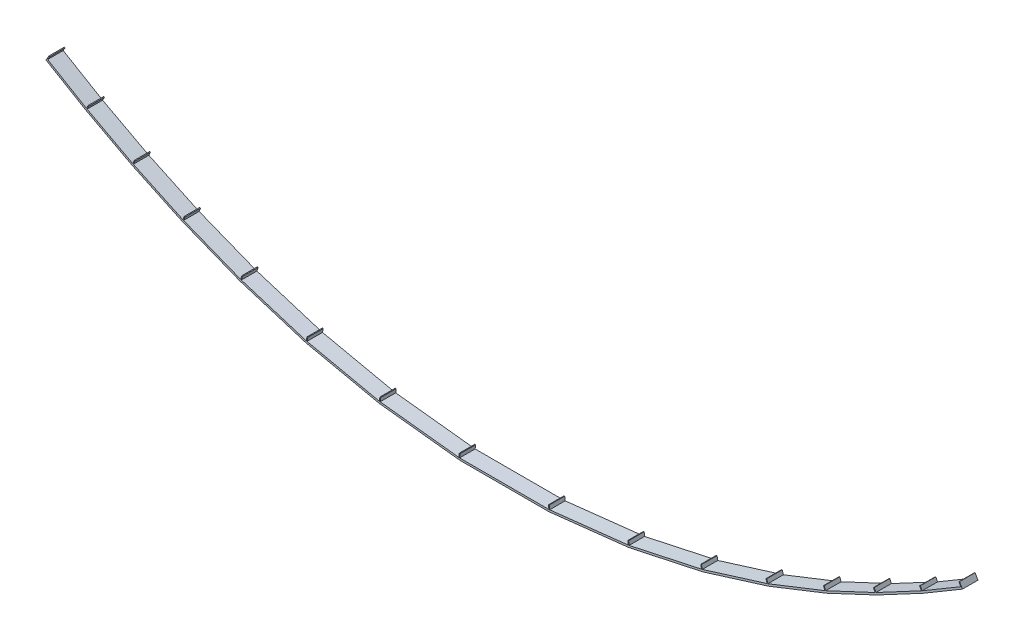
SolidWorks part; units mm, degrees
ref_plane "前视基准面" through (0, 0, 0) normal (0, 0, 1) x (1, 0, 0)
ref_plane "上视基准面" through (0, 0, 0) normal (0, 1, 0) x (1, 0, 0)
ref_plane "右视基准面" through (0, 0, 0) normal (1, 0, 0) x (0, 0, -1)
other "Configuration Table"
sketch "草图1" plane through (0, 0, 0) normal (0, 0, 1) x (1, 0, 0)
  line L0 (-115, 0) -> (115, 0)
  line L1 (-115, 0) -> (-321.7118, 23.1134)
  line L2 (-321.7118, 23.1134) -> (-510.3602, 63.8661)
  line L3 (-510.3602, 63.8661) -> (-679.3804, 116.413)
  line L4 (-679.3804, 116.413) -> (-828.1857, 175.2091)
  line L5 (-828.1857, 175.2091) -> (-957.6609, 235.9148)
  line L6 (-957.6609, 235.9148) -> (-1076.8145, 299.3766)
  line L7 (-1076.8145, 299.3766) -> (-1178.3926, 359.4258)
  line L8 (-1079.2632, 295.0159) -> (-1180.937, 355.1216)
  line L9 (-959.8988, 231.4418) -> (-1079.2632, 295.0159)
  line L10 (-830.1676, 170.616) -> (-959.8988, 231.4418)
  line L11 (-681.0436, 111.694) -> (-830.1676, 170.616)
  line L12 (-511.6328, 59.0257) -> (-681.0436, 111.694)
  line L13 (-322.5196, 18.1725) -> (-511.6328, 59.0257)
  line L14 (-115.2787, -5) -> (-322.5196, 18.1725)
  line L15 (-115.2787, -5) -> (115, -5)
  line L16 (115, 0) -> (115, -5)
  line L17 (0, 0) -> (0, -3) construction
  line L18 (-1178.3926, 359.4258) -> (-1180.937, 355.1216)
  dimension "D1" = 230
  dimension "D2" = 115
  dimension "D3" = 208
  dimension "D4" = 173.62
  dimension "D5" = 167.81
  dimension "D6" = 193
  dimension "D7" = 162.73
  dimension "D8" = 177
  dimension "D9" = 158.44
  dimension "D10" = 160
  dimension "D11" = 154.88
  dimension "D12" = 143
  dimension "D13" = 135
  dimension "D14" = 151.96
  dimension "D15" = 149.41
  dimension "D16" = 118
  dimension "D17" = 5
extrude "凸台-拉伸1" add sketch "草图1" along normal blind 40
sketch "草图2" plane through (0, 0, 40) normal (0, 0, 1) x (1, 0, 0)
  line L0 (-115, 0) -> (-113.8888, 9.9381)
  line L1 (-113.8888, 9.9381) -> (-115.8764, 10.1603)
  line L2 (-115.8764, 10.1603) -> (-116.9876, 0.2222)
  line L3 (-115, 0) -> (-321.7118, 23.1134) construction
  line L4 (-321.7118, 23.1134) -> (-320.6006, 33.0515)
  line L5 (-320.6006, 33.0515) -> (-318.613, 32.8292)
  line L6 (-318.613, 32.8292) -> (-319.7242, 22.8911)
  line L7 (-510.3602, 63.8661) -> (-508.2486, 73.6407)
  line L8 (-508.2486, 73.6407) -> (-506.2937, 73.2184)
  line L9 (-506.2937, 73.2184) -> (-508.4053, 63.4438)
  line L10 (-321.7118, 23.1134) -> (-510.3602, 63.8661) construction
  line L11 (-679.3804, 116.413) -> (-676.4116, 125.9622)
  line L12 (-676.4116, 125.9622) -> (-674.5018, 125.3684)
  line L13 (-674.5018, 125.3684) -> (-677.4706, 115.8193)
  line L14 (-510.3602, 63.8661) -> (-679.3804, 116.413) construction
  line L15 (-828.1857, 175.2091) -> (-824.511, 184.5094)
  line L16 (-824.511, 184.5094) -> (-822.6509, 183.7744)
  line L17 (-822.6509, 183.7744) -> (-826.3256, 174.4741)
  line L18 (-679.3804, 116.413) -> (-828.1857, 175.2091) construction
  line L19 (-957.6609, 235.9148) -> (-953.4157, 244.969)
  line L20 (-953.4157, 244.969) -> (-951.6049, 244.12)
  line L21 (-951.6049, 244.12) -> (-955.85, 235.0657)
  line L22 (-828.1857, 175.2091) -> (-957.6609, 235.9148) construction
  line L23 (-1076.8145, 299.3766) -> (-1072.1136, 308.2028)
  line L24 (-1072.1136, 308.2028) -> (-1070.3484, 307.2627)
  line L25 (-1070.3484, 307.2627) -> (-1075.0493, 298.4365)
  line L26 (-957.6609, 235.9148) -> (-1076.8145, 299.3766) construction
  line L27 (-1178.3926, 359.4258) -> (-1173.3036, 368.0341)
  line L28 (-1173.3036, 368.0341) -> (-1171.582, 367.0163)
  line L29 (-1171.582, 367.0163) -> (-1176.6709, 358.408)
  line L30 (-1076.8145, 299.3766) -> (-1178.3926, 359.4258) construction
  line L31 (-1178.3926, 359.4258) -> (-1176.6709, 358.408)
  line L32 (-1076.8145, 299.3766) -> (-1075.0493, 298.4365)
  line L33 (-957.6609, 235.9148) -> (-955.85, 235.0657)
  line L34 (-828.1857, 175.2091) -> (-826.3256, 174.4741)
  line L35 (-679.3804, 116.413) -> (-677.4706, 115.8193)
  line L36 (-510.3602, 63.8661) -> (-508.4053, 63.4438)
  line L37 (-321.7118, 23.1134) -> (-319.7242, 22.8911)
  line L38 (-116.9876, 0.2222) -> (-115, 0)
  dimension "D1" = 10
  dimension "D2" = 2
  dimension "D3" = 2
  dimension "D4" = 10
  dimension "D5" = 2
  dimension "D6" = 10
  dimension "D7" = 2
  dimension "D8" = 10
  dimension "D9" = 10
  dimension "D10" = 2
  dimension "D11" = 10
  dimension "D12" = 2
  dimension "D13" = 2
  dimension "D14" = 10
  dimension "D15" = 2
  dimension "D16" = 10
extrude "凸台-拉伸2" add sketch "草图2" against normal blind 40
mirror "镜向1" about plane through (0, 0, 0) normal (1, 0, 0) of "凸台-拉伸2", "凸台-拉伸1"
